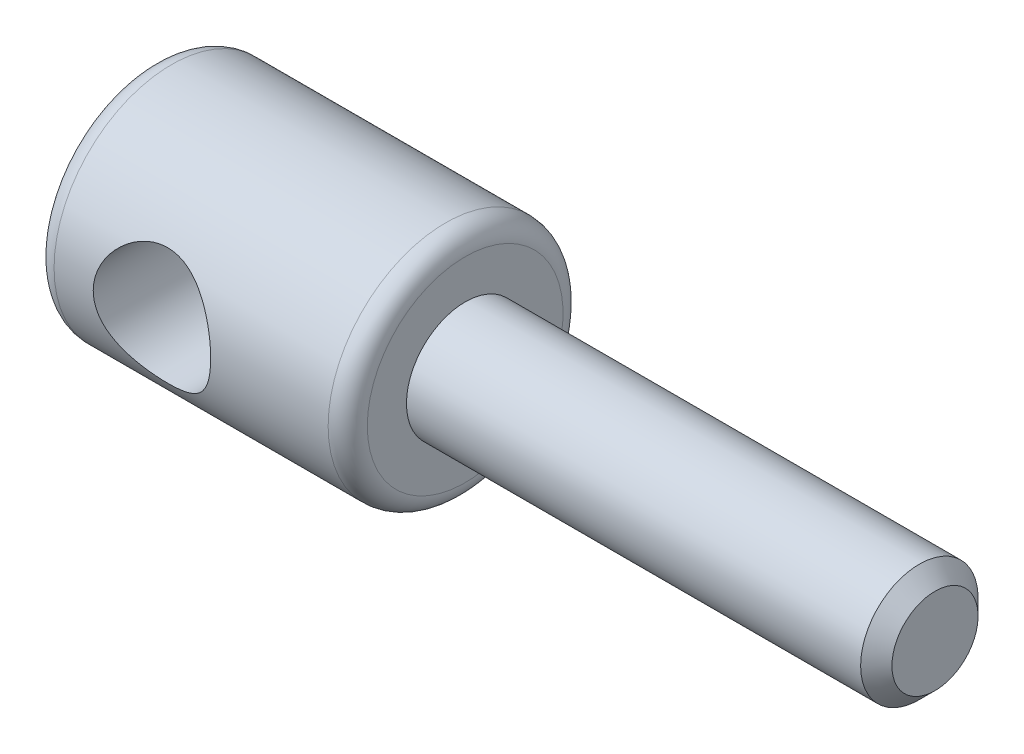
SolidWorks part; units mm, degrees
material "AISI 1015 Steel, Cold Drawn (SS)"
ref_plane "Front" through (0, 0, 0) normal (0, 0, 1) x (1, 0, 0)
ref_plane "Top" through (0, 0, 0) normal (0, 1, 0) x (1, 0, 0)
ref_plane "Right" through (0, 0, 0) normal (1, 0, 0) x (0, 0, -1)
sketch "Sketch1" plane through (0, 0, 0) normal (0, 0, 1) x (1, 0, 0)
  line L0 (-10.4443, 0) -> (72.0546, 0) construction
  line L1 (0, 0) -> (0, 9.525)
  line L2 (0, 9.525) -> (25.4, 9.525)
  line L3 (25.4, 9.525) -> (25.4, 4.7625)
  line L4 (25.4, 4.7625) -> (63.5, 4.7625)
  line L5 (63.5, 4.7625) -> (63.5, 0)
  line L6 (63.5, 0) -> (0, 0)
  dimension "D3" = 19.05
  dimension "D1" = 63.5
  dimension "D2" = 25.4
  dimension "D4" = 9.525
revolve "Revolve1" add sketch "Sketch1" angle 360 about L0
cosmetic thread "Cosmetic Thread8" parameters "D1"=25.4, "D2"=7.6327
fillet "Fillet1" radius 1.5875 2 edges at (25.4, 0, 9.525) (0, 0, 9.525)
ref_plane "Plane1" through (0, 0, 10.16) normal (0, 0, 1) x (1, 0, 0)
sketch "Sketch2" plane through (0, 0, 10.16) normal (0, 0, 1) x (1, 0, 0)
  line L0 (0, 7.9375) -> (0, -7.9375) construction
  circle A0 centre (9.525, 0) radius 4.7625
  dimension "D1" = 9.525
  dimension "D2" = 9.525
extrude "Cut-Extrude2" cut sketch "Sketch2" against normal through all
chamfer "Chamfer1" distance 1.27 angle 45 1 edges at (63.5, 0, 4.7625)
